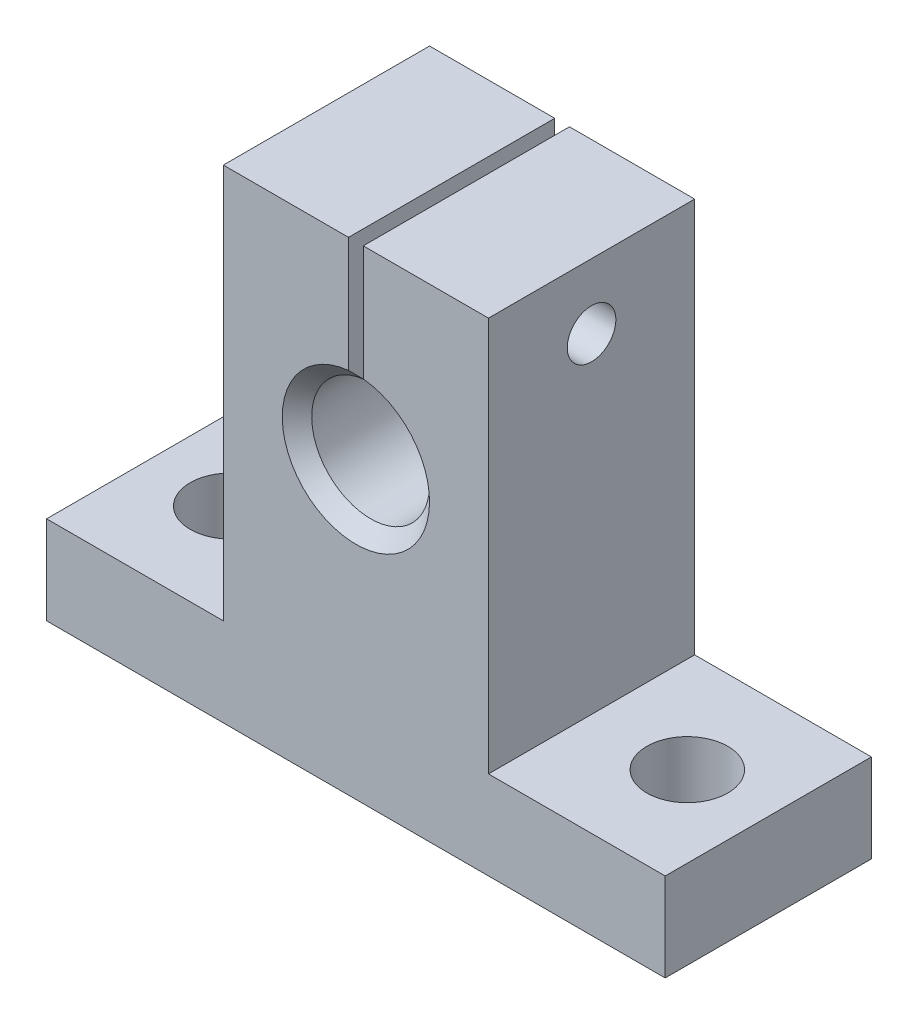
SolidWorks part; units mm, degrees
ref_plane "Front Plane" through (0, 0, 0) normal (0, 0, 1) x (1, 0, 0)
ref_plane "Top Plane" through (0, 0, 0) normal (0, 1, 0) x (1, 0, 0)
ref_plane "Right Plane" through (0, 0, 0) normal (1, 0, 0) x (0, 0, -1)
sketch "Sketch1" plane through (0, 0, 0) normal (0, 0, 1) x (1, 0, 0)
  line L0 (0, 0) -> (0, 38483.9964) construction
  line L1 (21, 0) -> (-21, 0)
  line L2 (-21, 0) -> (-21, 6)
  line L3 (-21, 6) -> (-9, 6)
  line L4 (-9, 6) -> (-9, 32.8)
  line L5 (-9, 32.8) -> (9, 32.8)
  line L6 (9, 6) -> (9, 32.8)
  line L7 (21, 6) -> (9, 6)
  line L8 (21, 0) -> (21, 6)
  point P10 (0, 32.8)
  point P13 (0, 0)
  dimension "D1" = 32.8
  dimension "D2" = 18
  dimension "D3" = 42
  dimension "D4" = 6
extrude "Boss-Extrude1" add sketch "Sketch1" along normal blind 14
sketch "Sketch2" plane through (0, 0, 14) normal (0, 0, 1) x (1, 0, 0)
  line L0 (0, 32.8) -> (0, 0) construction
  line L1 (9, 32.8) -> (-9, 32.8) construction
  line L2 (-21, 0) -> (21, 0) construction
  circle A0 centre (0, 20) radius 4
  dimension "D1" = 8
  dimension "D2" = 20
extrude "Cut-Extrude1" cut sketch "Sketch2" against normal through all
sketch "Sketch3" plane through (0, 0, 14) normal (0, 0, 1) x (1, 0, 0)
  line L0 (0, 24) -> (0, 32.8) construction
  line L1 (9, 32.8) -> (-9, 32.8) construction
  line L3 (-0.5, 20.9) -> (0.5, 20.9)
  line L4 (-0.5, 20.9) -> (-0.5, 35.9)
  line L5 (-0.5, 35.9) -> (0.5, 35.9)
  line L6 (0.5, 20.9) -> (0.5, 35.9)
  line L7 (-0.5, 20.9) -> (0.5, 35.9) construction
  line L8 (-0.5, 35.9) -> (0.5, 20.9) construction
  circle A0 centre (0, 20) radius 4 construction
  point P6 (0, 28.4)
  dimension "D1" = 1
  dimension "D2" = 15
extrude "Cut-Extrude2" cut sketch "Sketch3" against normal through all
sketch "Sketch4" plane through (0, 6, 0) normal (0, 1, 0) x (1, 0, 0)
  line L0 (-21, -7) -> (21, -7) construction
  line L1 (-21, -14) -> (-21, 0) construction
  line L2 (21, -14) -> (21, 0) construction
  line L3 (0, 0) -> (0, -14) construction
  line L4 (-4, -14) -> (4, -14) construction
  circle A0 centre (-15.5, -7) radius 2.75
  circle A1 centre (15.5, -7) radius 2.75
  dimension "D1" = 31
  dimension "D2" = 5.5
extrude "Cut-Extrude3" cut sketch "Sketch4" against normal through all
chamfer "Chamfer1" distance 1 angle 45 2 edges at (0, 16, 14) (0, 16, 0)
sketch "Sketch6" plane through (-9, 0, 0) normal (-1, 0, 0) x (0, 0, 1)
  line L0 (7, 32.8) -> (7, 23.9686) construction
  line L1 (14, 32.8) -> (0, 32.8) construction
  line L2 (1, 23.9686) -> (13, 23.9686) construction
  circle A0 centre (7, 28.3843) radius 2.5
  dimension "D1" = 5
hole_wizard "CBORE for M4 Hex Socket Head Cap Screw1" positions "Sketch9" profile "Sketch8" counterbore size "M4" standard "ISO"
sketch "Sketch9" plane through (-9, 0, 0) normal (-1, 0, 0) x (0, 0, 1)
  point P0 (7, 28.3843)
sketch "Sketch8" plane through (-9, 28.3843, 7) normal (0, 1, 0) x (0, 0, 1)
  line L0 (0, 0) -> (0, 11.4519)
  line L1 (0, 11.4519) -> (2.25, 10.1)
  line L2 (2.25, 10.1) -> (2.25, 4.4)
  line L3 (2.25, 4.4) -> (3.75, 4.4)
  line L4 (3.75, 4.4) -> (3.75, 0)
  line L5 (3.75, 0) -> (0, 0)
  line L10 (0, 11.4519) -> (-2.25, 10.1) construction
  line L11 (0, -6.35) -> (0, 107.95) construction
  dimension "Hole Dia." = 4.5
  dimension "Hole Depth" = 10.1
  dimension "C'Bore Dia." = 7.5
  dimension "C'Bore Depth" = 4.4
  dimension "Drill Angle" = 118
hole_wizard "M4 Tapped Hole1" positions "Sketch10" profile "Sketch11" tap size "M4" standard "ISO"
sketch "Sketch10" plane through (0.5, 0, 0) normal (-1, 0, 0) x (0, 0, 1)
  point P0 (7, 28.3843)
sketch "Sketch11" plane through (0.5, 28.3843, 7) normal (0, 1, 0) x (0, 0, 1)
  line L0 (0, 0) -> (0, 11.0914)
  line L1 (0, 11.0914) -> (1.65, 10.1)
  line L2 (1.65, 10.1) -> (1.65, 0)
  line L5 (1.65, 0) -> (0, 0)
  line L10 (0, 11.0914) -> (-1.65, 10.1) construction
  line L11 (0, -6.35) -> (0, 107.95) construction
  dimension "Tap Drill Dia." = 3.3
  dimension "Tap Drill Depth" = 10.1
  dimension "Drill Angle" = 118
cosmetic thread "Hole Thread1" parameters "D1"=8, "D2"=4
sketch "Sketch13" plane through (-9, 0, 0) normal (-1, 0, 0) x (0, 0, 1)
  line L0 (0, 11.0412) -> (14, 11.0412) construction
  line L1 (0, 32.8) -> (0, 6) construction
  line L2 (14, 32.8) -> (14, 6) construction
  text T0 "SK8"
extrude "Cut-Extrude5" cut sketch "Sketch13" against normal blind 1
